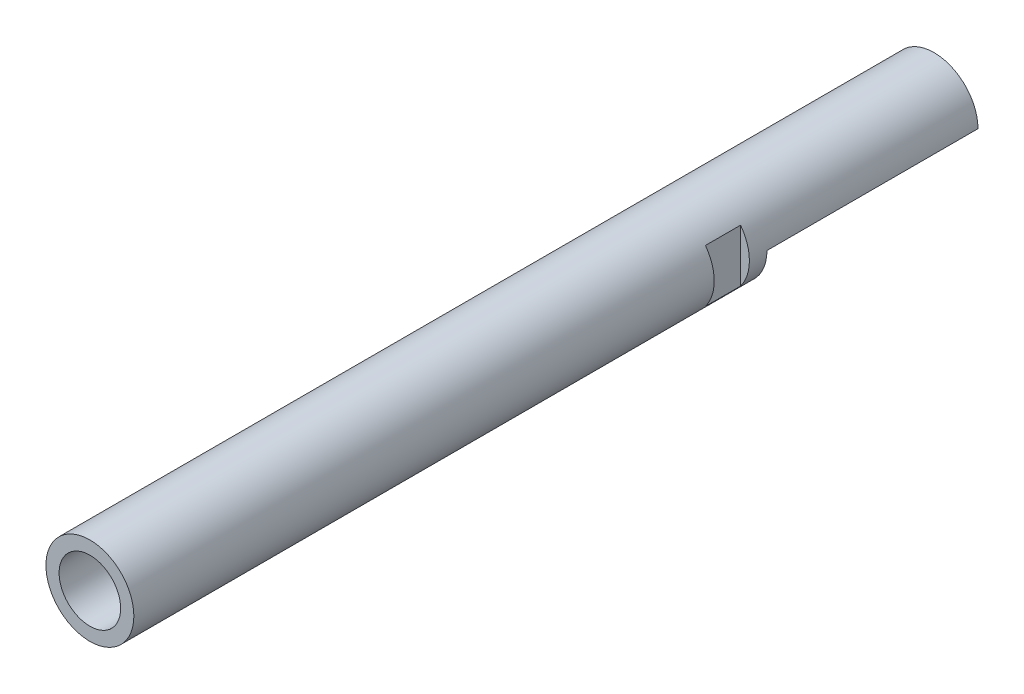
SolidWorks part; units mm, degrees
ref_plane "Front" through (0, 0, 0) normal (0, 0, 1) x (1, 0, 0)
ref_plane "Top" through (0, 0, 0) normal (0, 1, 0) x (1, 0, 0)
ref_plane "Right" through (0, 0, 0) normal (1, 0, 0) x (0, 0, -1)
sketch "Sketch1" plane through (0, 0, 0) normal (0, 0, 1) x (1, 0, 0)
  circle A0 centre (0, 0) radius 9.525
  circle A1 centre (0, 0) radius 15.875
  dimension "D1" = 19.05
  dimension "D2" = 31.75
extrude "Boss-Extrude1" add sketch "Sketch1" along normal blind 304.8
sketch "Sketch2" plane through (0, 0, 304.8) normal (0, 0, 1) x (1, 0, 0)
  circle A0 centre (0, 0) radius 11.1125
  dimension "D1" = 22.225
extrude "Cut-Extrude1" cut sketch "Sketch2" against normal blind 19.05
sketch "Sketch6" plane through (0, 0, 0) normal (0, 0, -1) x (-1, 0, 0)
  line L0 (15.875, 0) -> (-15.875, 0)
  circle A0 centre (0, 0) radius 15.875 construction
  circle A2 centre (0, 0) radius 15.875
  arc A3 (-15.875, 0) -> (15.875, 0) centre (0, 0) ccw
  dimension "D1" = 0
extrude "Cut-Extrude4" cut sketch "Sketch6" against normal blind 76.2
ref_plane "Plane1" through (0, 0, 82.55) normal (0, 0, -1) x (-1, 0, 0)
sketch "Sketch8" plane through (0, 0, 82.55) normal (0, 0, -1) x (-1, 0, 0)
  line L1 (12.7, 12.7) -> (-12.7, 12.7)
  line L2 (12.7, 12.7) -> (12.7, -12.7)
  line L3 (12.7, -12.7) -> (-12.7, -12.7)
  line L4 (-12.7, 12.7) -> (-12.7, -12.7)
  line L5 (12.7, 12.7) -> (-12.7, -12.7) construction
  line L6 (12.7, -12.7) -> (-12.7, 12.7) construction
  circle A1 centre (0, 0) radius 15.875
  circle A2 centre (0, 0) radius 15.875
  dimension "D2" = 25.4
  dimension "D1" = 0
extrude "Cut-Extrude7" cut sketch "Sketch8" against normal blind 12.7 contours L3 A2 | L4 A2
sketch "Sketch9" plane through (0, -12.7, 0) normal (0, -1, 0) x (1, 0, 0)
  line L0 (0, 95.25) -> (0, 304.8) construction
  line L1 (-9.525, 95.25) -> (9.525, 95.25) construction
  line L2 (15.875, 304.8) -> (-15.875, 304.8) construction
  line L3 (-9.525, 95.25) -> (9.525, 95.25) construction
  circle A0 centre (0, 107.95) radius 3.175
  circle A1 centre (0, 171.45) radius 3.175
  dimension "D1" = 76.2
  dimension "D2" = 12.7
  dimension "D3" = 6.35
extrude "Cut-Extrude8" cut sketch "Sketch9" against normal up to next and the other way up to next contours A1 L0 | L0 A1
sketch "Sketch10" plane through (0, 0, 0) normal (0, 0, -1) x (-1, 0, 0)
  line L2 (-15.875, 0) -> (-9.525, 0)
  line L3 (9.525, 0) -> (15.875, 0)
  line L4 (-15.875, 0) -> (-9.525, 0)
  line L5 (9.525, 0) -> (15.875, 0)
  arc A2 (15.875, 0) -> (-15.875, 0) centre (0, 0) ccw
  arc A3 (9.525, 0) -> (-9.525, 0) centre (0, 0) ccw
  arc A4 (15.875, 0) -> (-15.875, 0) centre (0, 0) ccw
  arc A5 (9.525, 0) -> (-9.525, 0) centre (0, 0) ccw
  dimension "D1" = 0
